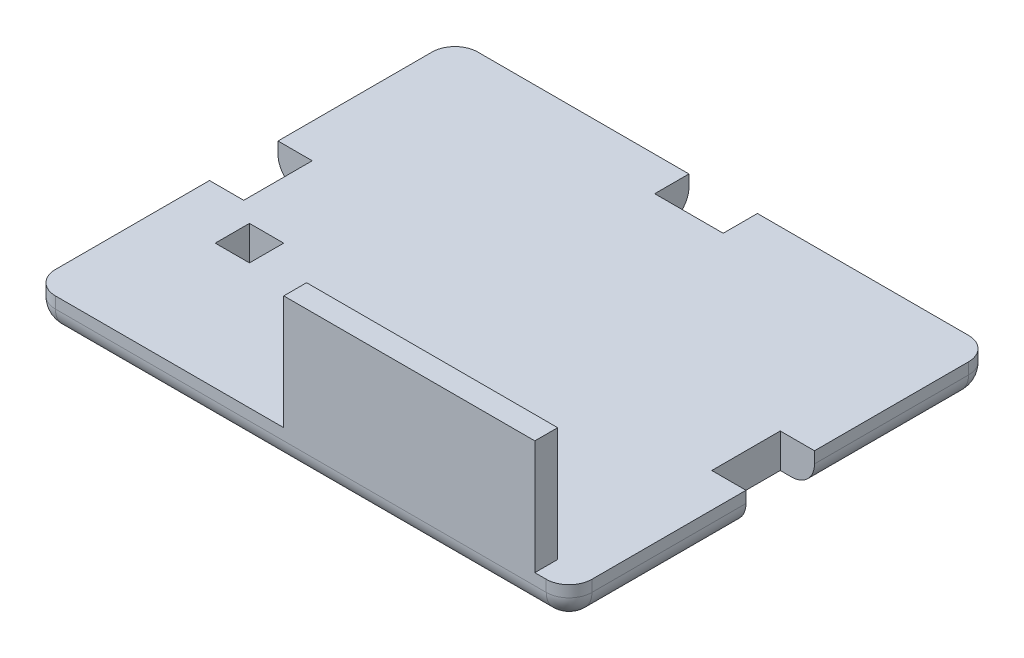
SolidWorks part; units mm, degrees
ref_plane "Front Plane" through (0, 0, 0) normal (0, 0, 1) x (1, 0, 0)
ref_plane "Top Plane" through (0, 0, 0) normal (0, 1, 0) x (1, 0, 0)
ref_plane "Right Plane" through (0, 0, 0) normal (1, 0, 0) x (0, 0, -1)
sketch "Sketch1" plane through (0, 0, 0) normal (0, 1, 0) x (1, 0, 0)
  line L1 (-17.7358, 10.9186) -> (5.7642, 10.9186)
  line L2 (-17.7358, 10.9186) -> (-17.7358, -7.5814)
  line L3 (-17.7358, -7.5814) -> (5.7642, -7.5814)
  line L4 (5.7642, 10.9186) -> (5.7642, -7.5814)
  dimension "D1" = 23.5
  dimension "D2" = 18.5
extrude "Boss-Extrude1" add sketch "Sketch1" along normal blind 1.5
sketch "Sketch2" plane through (0, 1.5, 0) normal (0, 1, 0) x (1, 0, 0)
  line L0 (5.7642, 10.9186) -> (-17.7358, 10.9186) construction
  line L4 (-7.4858, 10.9186) -> (-4.4858, 10.9186)
  line L5 (-7.4858, 10.9186) -> (-7.4858, 9.4186)
  line L6 (-7.4858, 9.4186) -> (-4.4858, 9.4186)
  line L7 (-4.4858, 10.9186) -> (-4.4858, 9.4186)
  line L8 (-17.7358, 10.9186) -> (-17.7358, -7.5814) construction
  line L9 (5.7642, -7.5814) -> (5.7642, 10.9186) construction
  line L10 (-17.7358, 3.1686) -> (-16.2358, 3.1686)
  line L11 (-17.7358, 3.1686) -> (-17.7358, 0.1686)
  line L12 (-17.7358, 0.1686) -> (-16.2358, 0.1686)
  line L13 (-16.2358, 3.1686) -> (-16.2358, 0.1686)
  line L14 (5.7642, 3.1686) -> (4.2642, 3.1686)
  line L15 (5.7642, 3.1686) -> (5.7642, 0.1686)
  line L16 (5.7642, 0.1686) -> (4.2642, 0.1686)
  line L17 (4.2642, 3.1686) -> (4.2642, 0.1686)
  dimension "D1" = 3
  dimension "D2" = 1.5
  dimension "D3" = 3
  dimension "D5" = 1.5
  dimension "D6" = 1.5
extrude "Cut-Extrude1" cut sketch "Sketch2" against normal blind 1.5
sketch "Sketch3" plane through (0, 1.5, 0) normal (0, 1, 0) x (1, 0, 0)
  line L1 (-17.7358, -7.5814) -> (5.7642, -7.5814) construction
  line L3 (4.2642, -7.5814) -> (-5.7358, -7.5814)
  line L4 (4.2642, -7.5814) -> (4.2642, -6.5814)
  line L5 (4.2642, -6.5814) -> (-5.7358, -6.5814)
  line L6 (-5.7358, -7.5814) -> (-5.7358, -6.5814)
  dimension "D1" = 10
  dimension "D3" = 1
extrude "Boss-Extrude2" add sketch "Sketch3" along normal blind 5 contours L4 L3 L6 L5
sketch "Sketch4" plane through (0, 0, 0) normal (0, -1, 0) x (1, 0, 0)
  line L9 (-1.1773, -2.3007) -> (-0.8886, -1.8007)
  line L10 (-0.8886, -1.8007) -> (-1.1773, -1.3007)
  line L17 (-5.9858, -5.989) -> (-5.4858, -5.7004)
  line L22 (-6.4858, -5.7004) -> (-5.9858, -5.989)
  line L23 (-1.7547, -1.3007) -> (-2.0433, -1.8007) [skipped]
  line L24 (-2.0433, -1.8007) -> (-1.7547, -2.3007) [skipped]
  line L25 (-5.9858, -4.8343) -> (-6.4858, -5.123) [skipped]
  line L26 (-5.4858, -5.123) -> (-5.9858, -4.8343) [skipped]
  line L27 (-1.1773, -1.3007) -> (-1.7547, -1.3007) [skipped]
  line L28 (-4.5716, -1.3007) -> (-1.1773, -1.3007)
  line L29 (-1.7547, -2.3007) -> (-1.1773, -2.3007) [skipped]
  line L30 (-4.5716, -2.3007) -> (-1.1773, -2.3007)
  line L31 (-6.4858, -5.123) -> (-6.4858, -5.7004) [skipped]
  line L32 (-6.4858, -3.2149) -> (-6.4858, -5.7004)
  line L33 (-5.4858, -5.7004) -> (-5.4858, -5.123) [skipped]
  line L34 (-5.4858, -3.2149) -> (-5.4858, -5.7004)
  arc A0 (-5.4858, -3.2149) -> (-4.5716, -2.3007) centre (-5.9858, -1.8007) ccw
  arc A1 (-4.5716, -1.3007) -> (-6.4858, -3.2149) centre (-5.9858, -1.8007) ccw
  text T0 "<b>X</b>" font "Century Gothic" height in points 10
  text T1 "<b>Z</b>" font "Century Gothic" height in points 10
  text T2 "<b>Y</b>" font "Century Gothic" height in points 10
  point P3 (-5.9858, -1.8007)
  point P7 (-5.9858, -1.8007)
extrude "Cut-Extrude3" cut sketch "Sketch4" against normal blind 0.75
sketch "Sketch5" plane through (0, 0, 0) normal (0, -1, 0) x (1, 0, 0)
  line L0 (-11.0684, 7.5814) -> (-11.0684, 0.5814)
  line L1 (-17.7358, 7.5814) -> (5.7642, 7.5814) construction
  line L5 (-13.7358, 0.5814) -> (-15.2358, 0.5814)
  line L6 (-13.7358, 0.5814) -> (-13.7358, 2.0814)
  line L7 (-13.7358, 2.0814) -> (-15.2358, 2.0814)
  line L8 (-15.2358, 0.5814) -> (-15.2358, 2.0814)
  dimension "D1" = 1.5
  dimension "D3" = 1.5
extrude "Cut-Extrude4" cut sketch "Sketch5" against normal blind 1.5 contours L8 L5 L6 L7
fillet "Fillet1" radius 1 6 edges at (5.7642, 0, -7.0436) (5.7642, 0.75, -10.9186) (0.6392, 0, -10.9186) (-12.6108, 0, -10.9186) (-17.7358, 0.75, -10.9186) (-17.7358, 0, -7.0436)
fillet "Fillet4" radius 1 5 edges at (5.7642, 0.75, 7.5814) (-17.7358, 0.75, 7.5814) (-17.7358, 0, 3.7064) (-5.9858, 0, 7.5814) (5.7642, 0, 3.7064)
sketch "Sketch7" plane through (0, 1.5, 0) normal (0, 1, 0) x (1, 0, 0)
  line L0 (-16.7358, -7.5814) -> (-5.7358, -7.5814) construction
  line L1 (-5.7358, -6.5814) -> (-6.734, -6.5814)
  line L2 (-5.7358, -6.5814) -> (-5.7358, -7.5814)
  line L3 (-5.7358, -7.5814) -> (-6.734, -7.5814)
  line L4 (-6.734, -6.5814) -> (-6.734, -7.5814)
  dimension "D1" = 1
extrude "Boss-Extrude3" add sketch "Sketch7" along normal blind 5
